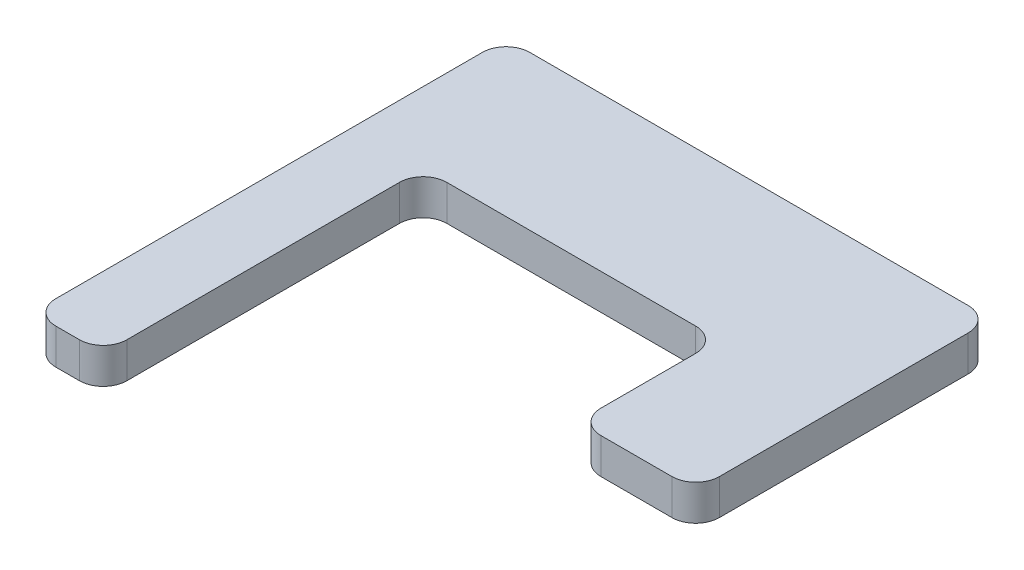
SolidWorks part; units mm, degrees
ref_plane "Front Plane" through (0, 0, 0) normal (0, 0, 1) x (1, 0, 0)
ref_plane "Top Plane" through (0, 0, 0) normal (0, 1, 0) x (1, 0, 0)
ref_plane "Right Plane" through (0, 0, 0) normal (1, 0, 0) x (0, 0, -1)
sketch "Sketch1" plane through (0, 0, 0) normal (0, 1, 0) x (1, 0, 0)
  line L0 (-19.3489, 6.0134) -> (21.6511, 6.0134)
  line L1 (21.6511, 6.0134) -> (21.6511, -18.9866)
  line L2 (21.6511, -18.9866) -> (11.6511, -18.9866)
  line L3 (11.6511, -18.9866) -> (11.6511, -6.9866)
  line L4 (11.6511, -6.9866) -> (-13.3489, -6.9866)
  line L5 (-13.3489, -6.9866) -> (-13.3489, -33.9866)
  line L6 (-13.3489, -33.9866) -> (-19.3489, -33.9866)
  line L7 (-19.3489, -33.9866) -> (-19.3489, 6.0134)
  point P6 (16.6511, -18.9866)
  dimension "D1" = 31
  dimension "D2" = 6
  dimension "D3" = 41
  dimension "D4" = 40
  dimension "D5" = 13
  dimension "D6" = 25
extrude "Boss-Extrude1" add sketch "Sketch1" along normal blind 3
fillet "Fillet1" radius 2 8 edges at (11.6511, 1.5, 6.9866) (-13.3489, 1.5, 6.9866) (21.6511, 1.5, -6.0134) (21.6511, 1.5, 18.9866) (11.6511, 1.5, 18.9866) (-13.3489, 1.5, 33.9866) (-19.3489, 1.5, 33.9866) (-19.3489, 1.5, -6.0134)
